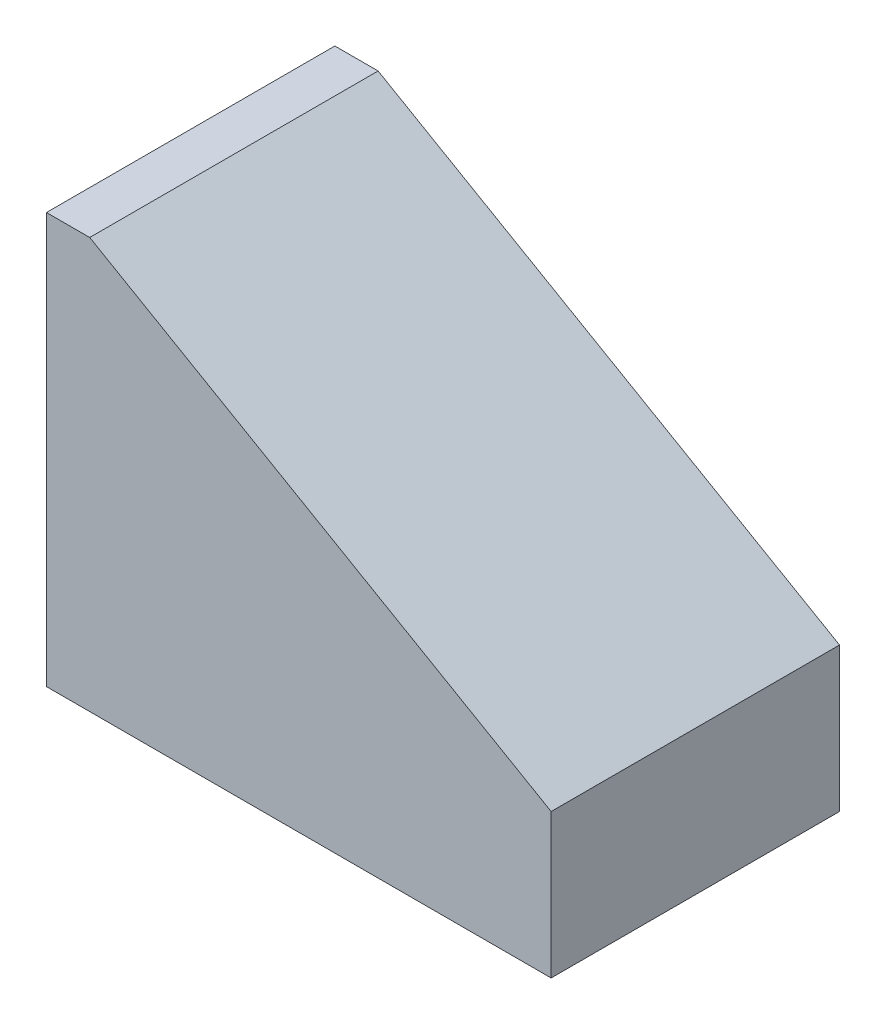
SolidWorks part; units mm, degrees
material "Oak"
ref_plane "Front Plane" through (0, 0, 0) normal (0, 0, 1) x (1, 0, 0)
ref_plane "Top Plane" through (0, 0, 0) normal (0, 1, 0) x (1, 0, 0)
ref_plane "Right Plane" through (0, 0, 0) normal (1, 0, 0) x (0, 0, -1)
sketch "Sketch1" plane through (0, 0, 0) normal (0, 0, 1) x (1, 0, 0)
  line L0 (0, 0) -> (-350, 0)
  line L1 (-350, 0) -> (-350, 284.7521)
  line L2 (-350, 284.7521) -> (-320, 284.7521)
  line L3 (-320, 284.7521) -> (0, 100)
  line L4 (0, 100) -> (0, 0)
  dimension "D1" = 350
  dimension "D2" = 100
  dimension "D3" = 30
  dimension "D4" = 30
extrude "Boss-Extrude1" add sketch "Sketch1" along normal mid plane 200
